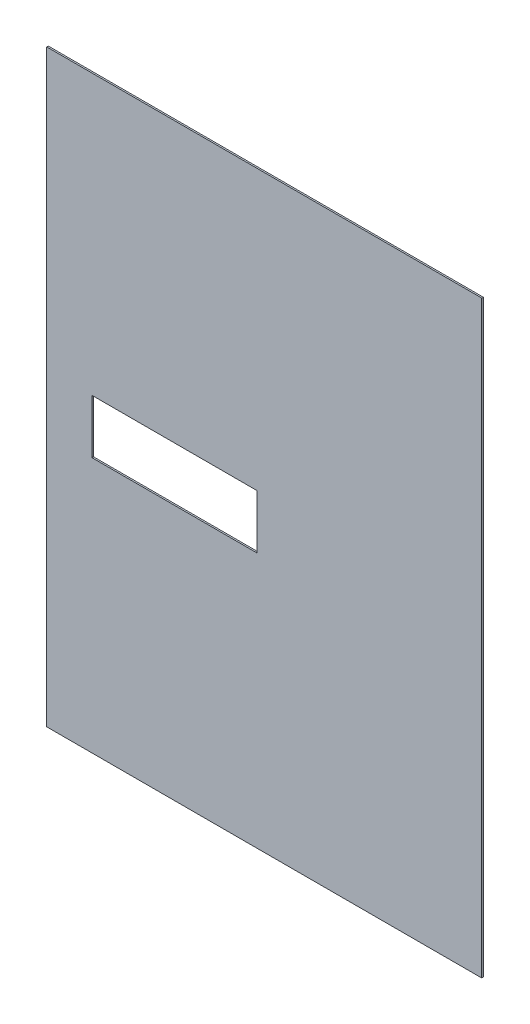
SolidWorks part; units mm, degrees
ref_plane "Front Plane" through (0, 0, 0) normal (0, 0, 1) x (1, 0, 0)
ref_plane "Top Plane" through (0, 0, 0) normal (0, 1, 0) x (1, 0, 0)
ref_plane "Right Plane" through (0, 0, 0) normal (1, 0, 0) x (0, 0, -1)
sketch "Sketch2" plane through (0, 0, 0) normal (0, 0, 1) x (1, 0, 0)
  line L1 (-535, 175) -> (535, 175)
  line L2 (-535, 175) -> (-535, -175)
  line L3 (-535, -175) -> (535, -175)
  line L4 (535, 175) -> (535, -175)
  line L5 (-535, 175) -> (535, -175) construction
  line L6 (-535, -175) -> (535, 175) construction
  line L7 (-828, -1831.9664) -> (1990.8053, -1831.9664)
  line L8 (-828, -1831.9664) -> (-828, 1983.6338)
  line L9 (-828, 1983.6338) -> (1990.8053, 1983.6338)
  line L10 (1990.8053, -1831.9664) -> (1990.8053, 1983.6338)
  point P0 (0, 0)
  dimension "D1" = 1070
  dimension "D2" = 350
  dimension "D3" = 293
extrude "Boss-Extrude1" add sketch "Sketch2" along normal blind 10
